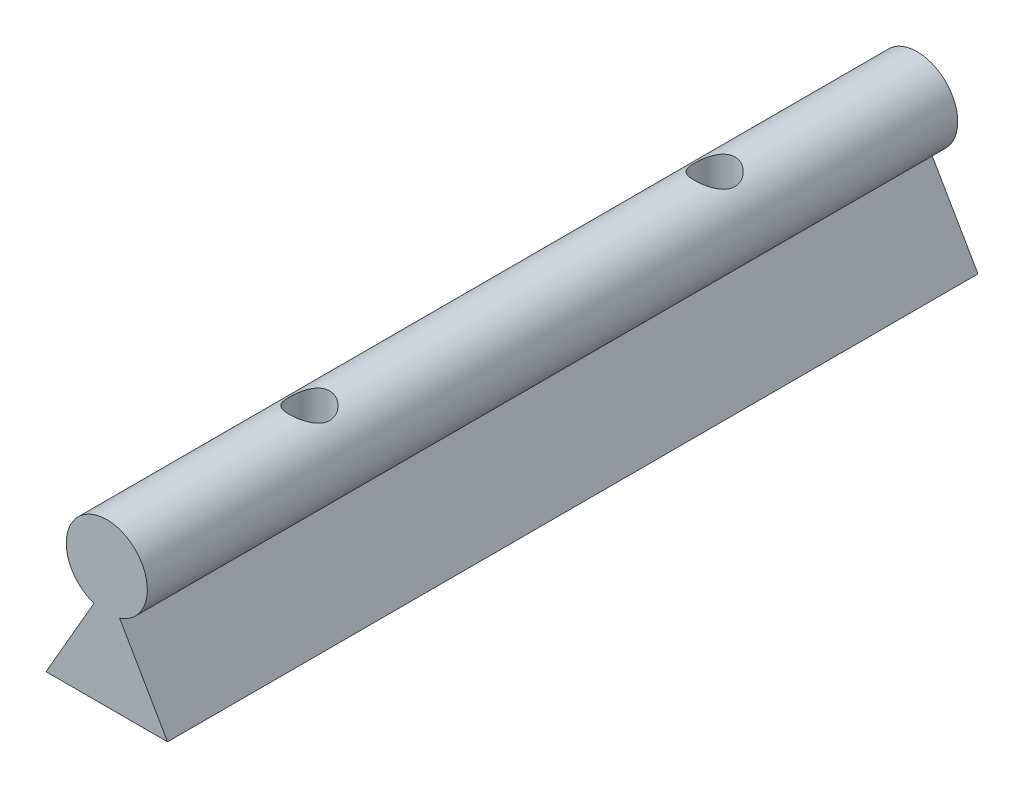
SolidWorks part; units mm, degrees
ref_plane "Front Plane" through (0, 0, 0) normal (0, 0, 1) x (1, 0, 0)
ref_plane "Top Plane" through (0, 0, 0) normal (0, 1, 0) x (1, 0, 0)
ref_plane "Right Plane" through (0, 0, 0) normal (1, 0, 0) x (0, 0, -1)
sketch "Sketch1" plane through (0, 0, 0) normal (0, 0, 1) x (1, 0, 0)
  line L0 (-19.05, 0) -> (19.05, 0)
  line L1 (0, 38.1) -> (0, 0) construction
  line L2 (-19.05, 0) -> (-4.0102, 26.0497)
  line L3 (4.0102, 26.0497) -> (19.05, 0)
  line L4 (19.05, 0) -> (19.05, 76.2) construction
  line L5 (19.05, 76.2) -> (-19.05, 76.2) construction
  line L6 (-19.05, 76.2) -> (-19.05, 0) construction
  arc A0 (4.0102, 26.0497) -> (-4.0102, 26.0497) centre (0, 38.1) ccw
  point P4 (0, 0)
  point P8 (19.05, 38.1)
  dimension "D2" = 25.4
  dimension "D1" = 38.1
  dimension "D3" = 60
  dimension "D5" = 76.2
extrude "Boss-Extrude1" add sketch "Sketch1" along normal blind 254
sketch "Sketch2" plane through (0, 0, 0) normal (0, -1, 0) x (1, 0, 0)
  line L0 (0, 254) -> (0, 0) construction
  line L1 (-19.05, 254) -> (19.05, 254) construction
  circle A0 centre (0, 190.5) radius 3.3274
  circle A1 centre (0, 63.5) radius 3.3274
  dimension "D1" = 6.6548
  dimension "D2" = 63.5
  dimension "D3" = 127
extrude "Cut-Extrude1" cut sketch "Sketch2" against normal through all
ref_plane "Plane1" through (0, 50.8, 0) normal (0, 1, 0) x (1, 0, 0)
sketch "Sketch3" plane through (0, 50.8, 0) normal (0, 1, 0) x (1, 0, 0)
  circle A0 centre (0, -63.5) radius 6.35
  circle A1 centre (0, -190.5) radius 6.35
  dimension "D1" = 12.7
extrude "Cut-Extrude2" cut sketch "Sketch3" against normal blind 12.7
